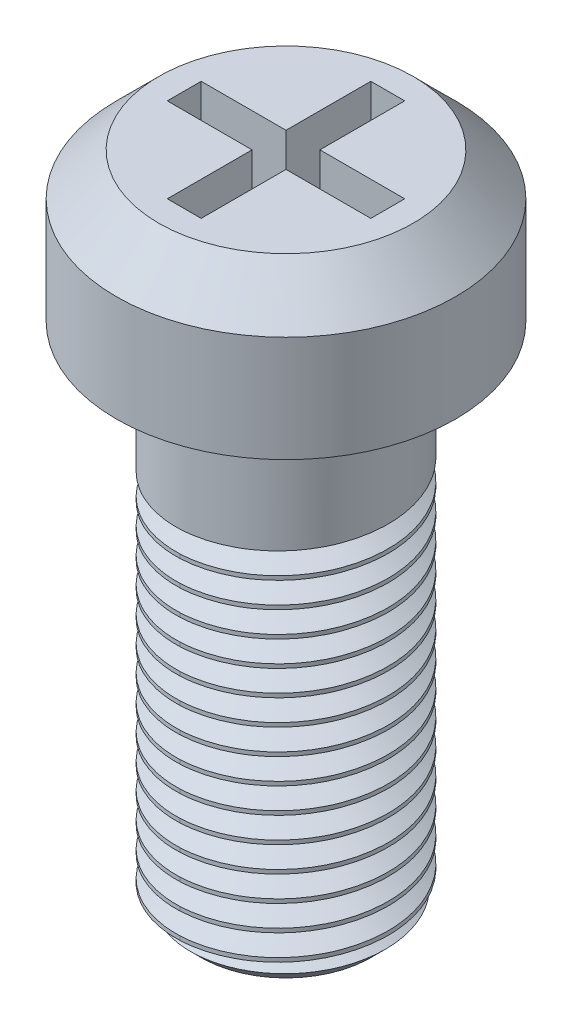
SolidWorks part; units mm, degrees
material "Stainless Steel (ferritic)"
ref_plane "Front" through (0, 0, 0) normal (0, 0, 1) x (1, 0, 0)
ref_plane "Top" through (0, 0, 0) normal (0, 1, 0) x (1, 0, 0)
ref_plane "Right" through (0, 0, 0) normal (1, 0, 0) x (0, 0, -1)
sketch "Sketch1" plane through (0, 0, 0) normal (0, 1, 0) x (1, 0, 0)
  circle A0 centre (0, 0) radius 2
  dimension "D1" = 4
extrude "Boss-Extrude1" add sketch "Sketch1" along normal blind 1.75
sketch "Sketch2" plane through (0, 0, 0) normal (0, -1, 0) x (-1, 0, 0)
  circle A0 centre (0, 0) radius 1.25
  dimension "D1" = 2.5
extrude "Boss-Extrude2" add sketch "Sketch2" along normal blind 6
ref_plane "Plane1" through (0, 1.75, 0) normal (0, 1, 0) x (1, 0, 0)
sketch "Sketch3" plane through (0, 1.75, 0) normal (0, 1, 0) x (1, 0, 0)
  line L0 (0, 2) -> (0, -2) construction
  line L1 (-2, 0) -> (2, 0) construction
  line L2 (-0.2, 1.2) -> (-0.2, 0.2)
  line L3 (-0.2, 0.2) -> (-1.2, 0.2)
  line L4 (0.2, 0.2) -> (1.2, 0.2)
  line L5 (0.2, 1.2) -> (0.2, 0.2)
  line L6 (0.2, -1.2) -> (0.2, -0.2)
  line L7 (0.2, -0.2) -> (1.2, -0.2)
  line L8 (-0.2, -0.2) -> (-1.2, -0.2)
  line L9 (-0.2, -1.2) -> (-0.2, -0.2)
  line L10 (-0.2, 1.2) -> (0.2, 1.2)
  line L11 (1.2, 0.2) -> (1.2, -0.2)
  line L12 (0.2, -1.2) -> (-0.2, -1.2)
  line L13 (-1.2, -0.2) -> (-1.2, 0.2)
  circle A0 centre (0, 0) radius 2 construction
  dimension "D1" = 1
  dimension "D2" = 0.2
  dimension "D3" = 0.2
extrude "Cut-Extrude1" cut sketch "Sketch3" against normal blind 1
chamfer "Chamfer1" distance 0.5 angle 45 1 edges at (0, 1.75, 2)
ref_plane "Plane2" through (0, 0, 0) normal (0, 0, 1) x (1, 0, 0)
ref_plane "Plane3" through (0, 0, 0) normal (0, -1, 0) x (-1, 0, 0)
chamfer "Chamfer2" distance 0.25 angle 45 1 edges at (0, -6, -1.25)
sketch "Sketch6" plane through (0, -6, 0) normal (0, -1, 0) x (-1, 0, 0)
  circle A0 centre (0, 0) radius 1.25
  dimension "D1" = 2.5
curve "Helix/Spiral1" pitch 0.3 height 4.5 turns 15
ref_plane "Plane4" through (0, 0, 0) normal (0, 0, 1) x (1, 0, 0)
sketch "Sketch8" plane through (0, 0, 0) normal (0, 0, 1) x (1, 0, 0)
  line L0 (-1.25, -5.75) -> (2.5432, -5.75) construction
  line L4 (1.0312, -5.7447) -> (1.4765, -6.0124)
  line L5 (1.4765, -6.0124) -> (1.4857, -5.4929)
  line L6 (1.4857, -5.4929) -> (1.0312, -5.7447)
  circle A1 centre (1.3311, -5.75) radius 0.15 construction
  dimension "D1" = 0.3
sweep "Cut-Sweep1" cut profiles "Sketch8" path "Helix/Spiral1"
